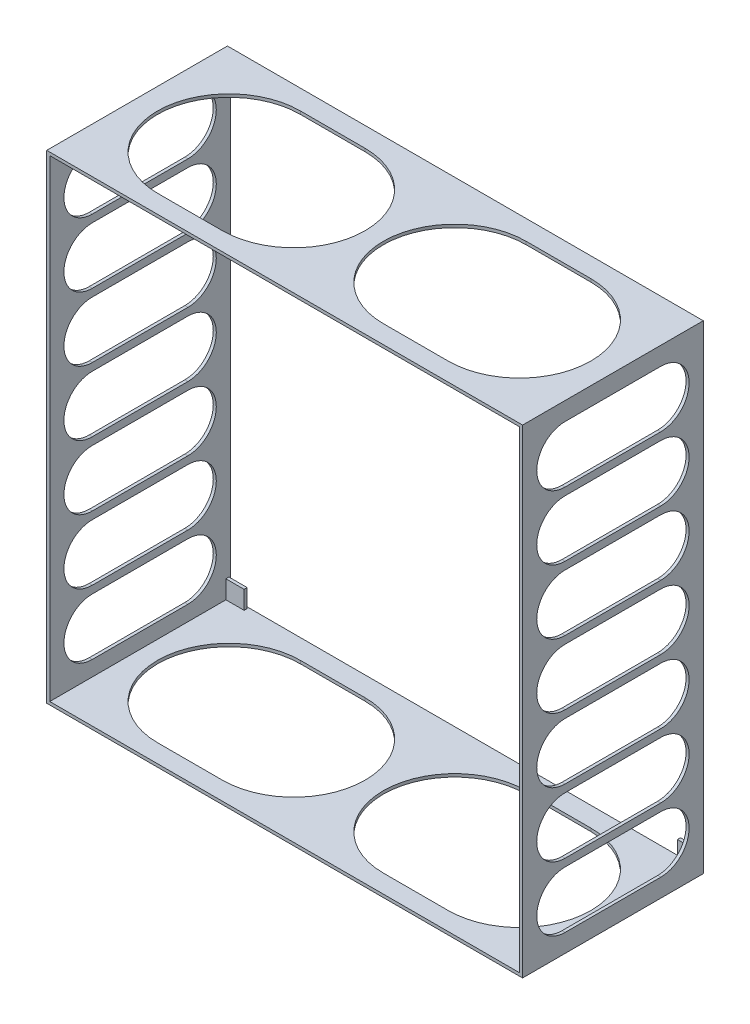
SolidWorks part; units mm, degrees
ref_plane "Front Plane" through (0, 0, 0) normal (0, 0, 1) x (1, 0, 0)
ref_plane "Top Plane" through (0, 0, 0) normal (0, 1, 0) x (1, 0, 0)
ref_plane "Right Plane" through (0, 0, 0) normal (1, 0, 0) x (0, 0, -1)
sketch "Sketch1" plane through (0, 0, 0) normal (0, 0, 1) x (1, 0, 0)
  line L1 (-20, -200) -> (289.367, -200)
  line L2 (-20, -200) -> (-20, 111.36)
  line L3 (-20, 111.36) -> (289.367, 111.36)
  line L4 (289.367, -200) -> (289.367, 111.36)
extrude "Extrude-Thin1" add sketch "Sketch1" along normal blind 119 thin
sketch "Sketch2" plane through (0, -200, 0) normal (0, 1, 0) x (1, 0, 0)
  line L0 (39, -60) -> (81.6835, -60) construction
  line L1 (39, -13) -> (81.6835, -13)
  line L2 (39, -107) -> (81.6835, -107)
  line L3 (187.6835, -60) -> (230.367, -60) construction
  line L4 (187.6835, -13) -> (230.367, -13)
  line L5 (187.6835, -107) -> (230.367, -107)
  line L6 (-20, -119) -> (-20, 0) construction
  line L7 (289.367, -119) -> (289.367, 0) construction
  line L8 (-20, -119) -> (289.367, -119) construction
  line L9 (-20, -1) -> (289.367, -1) construction
  arc A0 (39, -13) -> (39, -107) centre (39, -60) ccw
  arc A1 (81.6835, -107) -> (81.6835, -13) centre (81.6835, -60) ccw
  arc A2 (187.6835, -13) -> (187.6835, -107) centre (187.6835, -60) ccw
  arc A3 (230.367, -107) -> (230.367, -13) centre (230.367, -60) ccw
  point P2 (60.3418, -60)
  point P7 (209.0253, -60)
  point P14 (140.6835, -60)
  point P15 (-8, -60)
  point P16 (277.367, -60)
  point P17 (128.6835, -60)
  dimension "D1" = 12
  dimension "D2" = 12
  dimension "D3" = 12
  dimension "D4" = 12
  dimension "D5" = 12
extrude "Cut-Extrude1" cut sketch "Sketch2" against normal through all both and the other way through all
sketch "Sketch3" plane through (-20, 0, 0) normal (1, 0, 0) x (0, 0, -1)
  line L0 (-119, -200) -> (0, -200) construction
  line L1 (-3, -200) -> (-1, -200)
  line L2 (-3, -200) -> (-3, -188)
  line L3 (-3, -188) -> (-1, -188)
  line L4 (-1, -200) -> (-1, -188)
  line L5 (-1, 111.36) -> (-1, -200) construction
  dimension "D1" = 2
  dimension "D2" = 12
extrude "Boss-Extrude1" add sketch "Sketch3" along normal blind 12
sketch "Sketch4" plane through (-20, 0, 0) normal (1, 0, 0) x (0, 0, -1)
  line L0 (-119, 111.36) -> (0, 111.36) construction
  line L1 (-1, 111.36) -> (-3, 111.36)
  line L2 (-1, 111.36) -> (-1, 99.36)
  line L3 (-1, 99.36) -> (-3, 99.36)
  line L4 (-3, 111.36) -> (-3, 99.36)
  line L5 (-1, -70.7733) -> (-1, -130.3867) construction
  dimension "D1" = 2
  dimension "D2" = 12
extrude "Boss-Extrude2" add sketch "Sketch4" along normal blind 12
sketch "Sketch5" plane through (289.367, 0, 0) normal (-1, 0, 0) x (0, 0, 1)
  line L1 (1, 111.36) -> (3, 111.36)
  line L2 (1, 111.36) -> (1, 99.36)
  line L3 (1, 99.36) -> (3, 99.36)
  line L4 (3, 111.36) -> (3, 99.36)
  dimension "D1" = 12
  dimension "D2" = 2
extrude "Boss-Extrude3" add sketch "Sketch5" along normal blind 12
sketch "Sketch6" plane through (289.367, 0, 0) normal (-1, 0, 0) x (0, 0, 1)
  line L0 (119, -200) -> (0, -200) construction
  line L1 (1, -200) -> (3, -200)
  line L2 (1, -200) -> (1, -188)
  line L3 (1, -188) -> (3, -188)
  line L4 (3, -200) -> (3, -188)
  line L5 (1, 111.36) -> (1, -200) construction
  dimension "D1" = 2
  dimension "D2" = 12
extrude "Boss-Extrude4" add sketch "Sketch6" along normal blind 12
sketch "Sketch7" plane through (291.367, 0, 0) normal (1, 0, 0) x (0, 0, -1)
  line L0 (-91, 82.6914) -> (-28, 82.6914) construction
  line L1 (-91, 101.36) -> (-28, 101.36)
  line L2 (-91, 64.0229) -> (-28, 64.0229)
  line L3 (-91, 40.3543) -> (-28, 40.3543) construction
  line L4 (-91, 59.0229) -> (-28, 59.0229)
  line L5 (-91, 21.6857) -> (-28, 21.6857)
  line L6 (-91, -1.9829) -> (-28, -1.9829) construction
  line L7 (-91, 16.6857) -> (-28, 16.6857)
  line L8 (-91, -20.6514) -> (-28, -20.6514)
  line L9 (-91, -44.32) -> (-28, -44.32) construction
  line L10 (-91, -25.6514) -> (-28, -25.6514)
  line L11 (-91, -62.9886) -> (-28, -62.9886)
  line L12 (-91, -86.6571) -> (-28, -86.6571) construction
  line L13 (-91, -67.9886) -> (-28, -67.9886)
  line L14 (-91, -105.3257) -> (-28, -105.3257)
  line L15 (-91, -128.9943) -> (-28, -128.9943) construction
  line L16 (-91, -110.3257) -> (-28, -110.3257)
  line L17 (-91, -147.6629) -> (-28, -147.6629)
  line L18 (-91, -171.3314) -> (-28, -171.3314) construction
  line L19 (-91, -152.6629) -> (-28, -152.6629)
  line L20 (-91, -190) -> (-28, -190)
  line L21 (-91, 82.6914) -> (-91, 40.3543) construction
  line L22 (-91, 40.3543) -> (-91, -1.9829) construction
  line L23 (-91, -1.9829) -> (-91, -44.32) construction
  line L24 (-91, -44.32) -> (-91, -86.6571) construction
  line L25 (-91, -86.6571) -> (-91, -128.9943) construction
  line L26 (-91, -128.9943) -> (-91, -171.3314) construction
  line L27 (-119, 113.36) -> (0, 113.36) construction
  line L28 (-119, -202) -> (0, -202) construction
  line L29 (-119, -202) -> (-119, 113.36) construction
  line L30 (0, -202) -> (0, 113.36) construction
  arc A0 (-91, 101.36) -> (-91, 64.0229) centre (-91, 82.6914) ccw
  arc A1 (-28, 64.0229) -> (-28, 101.36) centre (-28, 82.6914) ccw
  arc A2 (-91, 59.0229) -> (-91, 21.6857) centre (-91, 40.3543) ccw
  arc A3 (-28, 21.6857) -> (-28, 59.0229) centre (-28, 40.3543) ccw
  arc A4 (-91, 16.6857) -> (-91, -20.6514) centre (-91, -1.9829) ccw
  arc A5 (-28, -20.6514) -> (-28, 16.6857) centre (-28, -1.9829) ccw
  arc A6 (-91, -25.6514) -> (-91, -62.9886) centre (-91, -44.32) ccw
  arc A7 (-28, -62.9886) -> (-28, -25.6514) centre (-28, -44.32) ccw
  arc A8 (-91, -67.9886) -> (-91, -105.3257) centre (-91, -86.6571) ccw
  arc A9 (-28, -105.3257) -> (-28, -67.9886) centre (-28, -86.6571) ccw
  arc A10 (-91, -110.3257) -> (-91, -147.6629) centre (-91, -128.9943) ccw
  arc A11 (-28, -147.6629) -> (-28, -110.3257) centre (-28, -128.9943) ccw
  arc A12 (-91, -152.6629) -> (-91, -190) centre (-91, -171.3314) ccw
  arc A13 (-28, -190) -> (-28, -152.6629) centre (-28, -171.3314) ccw
  point P2 (-59.5, 82.6914)
  point P7 (-59.5, 40.3543)
  point P14 (-59.5, -1.9829)
  point P21 (-59.5, -44.32)
  point P28 (-59.5, -86.6571)
  point P35 (-59.5, -128.9943)
  point P42 (-59.5, -171.3314)
  dimension "D4" = 28
  dimension "D1" = 12
  dimension "D2" = 12
  dimension "D3" = 28
  dimension "D5" = 5
extrude "Cut-Extrude2" cut sketch "Sketch7" against normal through all
